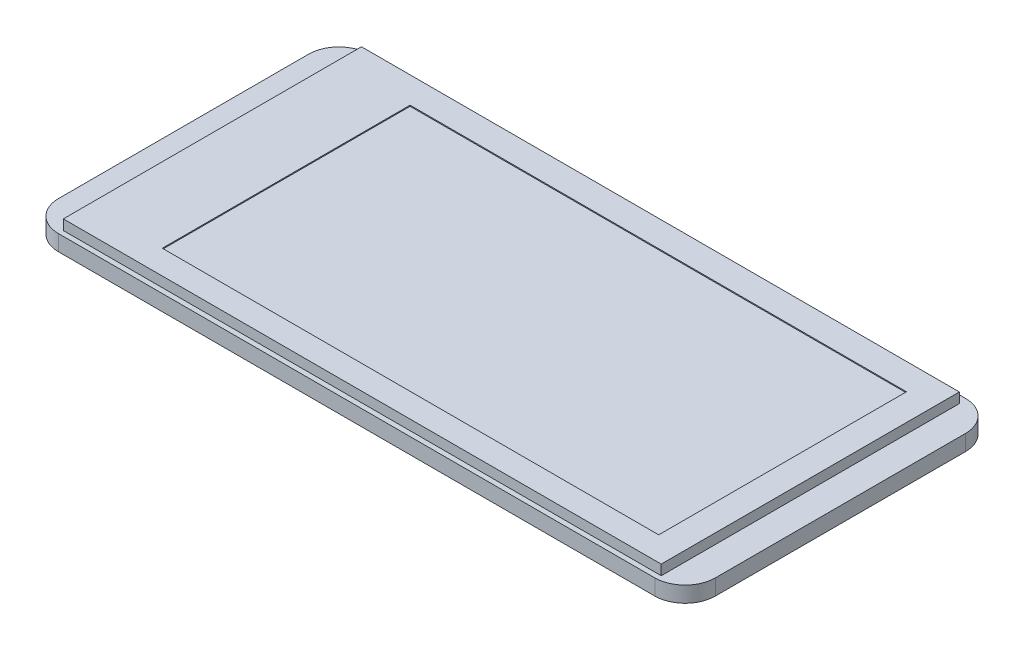
SolidWorks part; units mm, degrees
ref_plane "前视基准面" through (0, 0, 0) normal (0, 0, 1) x (1, 0, 0)
ref_plane "上视基准面" through (0, 0, 0) normal (0, 1, 0) x (1, 0, 0)
ref_plane "右视基准面" through (0, 0, 0) normal (1, 0, 0) x (0, 0, -1)
sketch "草图1" plane through (0, 0, 0) normal (0, 1, 0) x (1, 0, 0)
  line L1 (-29.5, 15.375) -> (29.5, 15.375)
  line L2 (-32.5, 12.375) -> (-32.5, -12.375)
  line L3 (-29.5, -15.375) -> (29.5, -15.375)
  line L4 (32.5, 12.375) -> (32.5, -12.375)
  line L5 (-32.5, 15.375) -> (32.5, -15.375) construction
  line L6 (-32.5, -15.375) -> (32.5, 15.375) construction
  arc A0 (-32.5, -12.375) -> (-29.5, -15.375) centre (-29.5, -12.375) ccw
  arc A1 (29.5, -15.375) -> (32.5, -12.375) centre (29.5, -12.375) ccw
  arc A2 (29.5, 15.375) -> (32.5, 12.375) centre (29.5, 12.375) cw
  arc A3 (-29.5, 15.375) -> (-32.5, 12.375) centre (-29.5, 12.375) ccw
  point P0 (0, 0)
  dimension "D3" = 3
  dimension "D1" = 30.75
  dimension "D2" = 65
extrude "凸台-拉伸1" add sketch "草图1" along normal blind 1.56
sketch "草图3" plane through (0, 1.56, 0) normal (0, 1, 0) x (1, 0, 0)
  line L0 (-29.5, -15.375) -> (29.5, -15.375) construction
  line L1 (-29.52, 14.625) -> (29.64, 14.625)
  line L2 (-29.52, 14.625) -> (-29.52, -14.875)
  line L3 (-29.52, -14.875) -> (29.64, -14.875)
  line L4 (29.64, 14.625) -> (29.64, -14.875)
  line L5 (-32.5, 12.375) -> (-32.5, -12.375) construction
  line L7 (32.5, -12.375) -> (32.5, 12.375) construction
  dimension "D1" = 29.5
  dimension "D2" = 2.98
  dimension "D3" = 0.5
  dimension "D4" = 2.86
extrude "凸台-拉伸2" add sketch "草图3" along normal blind 1
sketch "草图8" plane through (0, 0, 0) normal (0, -1, 0) x (1, 0, 0)
  line L0 (29.5, -15.375) -> (-29.5, -15.375) construction
  line L1 (-25.7, -8.735) -> (25.3, -8.735)
  line L2 (-25.7, -8.735) -> (-25.7, -13.735)
  line L3 (-25.7, -13.735) -> (25.3, -13.735)
  line L4 (25.3, -8.735) -> (25.3, -13.735)
  line L5 (32.5, 12.375) -> (32.5, -12.375) construction
  dimension "D1" = 5
  dimension "D2" = 51
  dimension "D3" = 1.64
  dimension "D4" = 7.2
extrude "凸台-拉伸6" add sketch "草图8" along normal blind 3.68
sketch "草图9" plane through (0, 2.56, 0) normal (0, 1, 0) x (1, 0, 0)
  line L0 (-32.5, 12.375) -> (-32.5, -12.375) construction
  line L1 (-22.11, 12.025) -> (27.01, 12.025)
  line L2 (-22.11, 12.025) -> (-22.11, -12.495)
  line L3 (-22.11, -12.495) -> (27.01, -12.495)
  line L4 (27.01, 12.025) -> (27.01, -12.495)
  line L5 (32.5, -12.375) -> (32.5, 12.375) construction
  line L6 (-29.5, -15.375) -> (29.5, -15.375) construction
  line L7 (29.5, 15.375) -> (-29.5, 15.375) construction
  dimension "D1" = 10.39
  dimension "D2" = 5.49
  dimension "D3" = 2.88
  dimension "D4" = 3.35
extrude "切除-拉伸1" cut sketch "草图9" against normal blind 0.1
